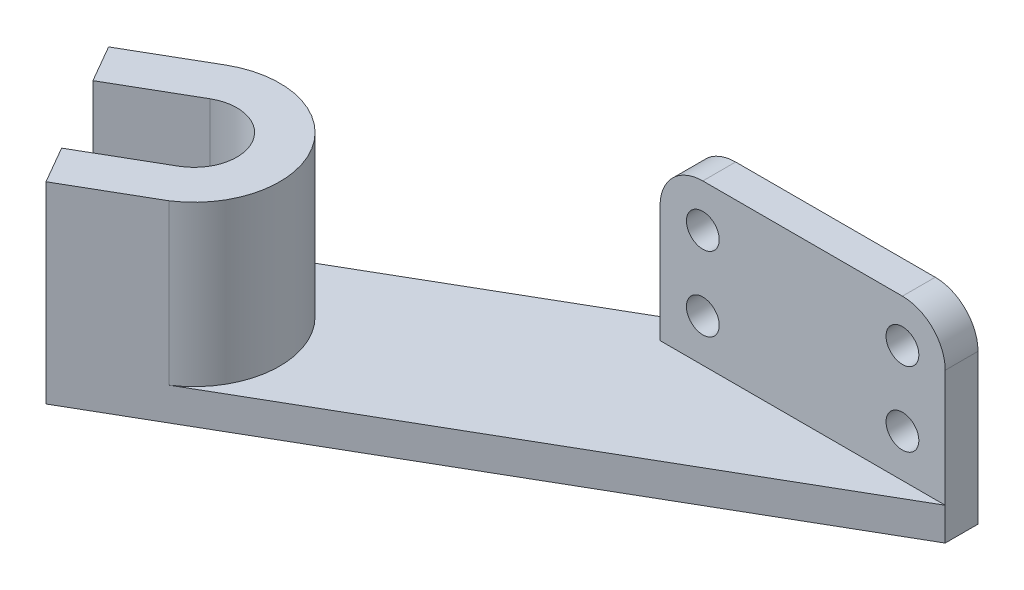
SolidWorks part; units mm, degrees
ref_plane "前视基准面" through (0, 0, 0) normal (0, 0, 1) x (1, 0, 0)
ref_plane "上视基准面" through (0, 0, 0) normal (0, 1, 0) x (1, 0, 0)
ref_plane "右视基准面" through (0, 0, 0) normal (1, 0, 0) x (0, 0, -1)
sketch "草图1" plane through (0, 0, 0) normal (0, 0, 1) x (1, 0, 0)
  line L1 (-50, 33.75) -> (50, 33.75)
  line L2 (-50, 33.75) -> (-50, -33.75)
  line L3 (-50, -33.75) -> (50, -33.75)
  line L4 (50, 33.75) -> (50, -33.75)
  line L5 (-50, 33.75) -> (50, -33.75) construction
  line L6 (-50, -33.75) -> (50, 33.75) construction
  point P0 (0, 0)
  dimension "D1" = 100
  dimension "D2" = 67.5
extrude "凸台-拉伸1" add sketch "草图1" along normal mid plane 11.5
fillet "圆角1" radius 15 2 edges at (50, 33.75, 0) (-50, 33.75, 0)
hole_wizard "Ø11.5 (11.5) 直径孔1" positions "草图2" profile "草图3" hole size "Ø11.5" standard "GB" end condition through all
sketch "草图2" plane through (0, 0, 5.75) normal (0, 0, 1) x (1, 0, 0)
  line L8 (50, -33.75) -> (50, 18.75)
  line L9 (35, 33.75) -> (-35, 33.75)
  line L10 (-50, 18.75) -> (-50, -33.75)
  line L11 (-50, -33.75) -> (50, -33.75)
  line L12 (50, -33.75) -> (50, 18.75)
  line L13 (35, 33.75) -> (-35, 33.75)
  line L14 (-50, 18.75) -> (-50, -33.75)
  line L15 (-50, -33.75) -> (50, -33.75)
  arc A4 (50, 18.75) -> (35, 33.75) centre (35, 18.75) ccw
  arc A5 (-35, 33.75) -> (-50, 18.75) centre (-35, 18.75) ccw
  arc A6 (50, 18.75) -> (35, 33.75) centre (35, 18.75) ccw
  arc A7 (-35, 33.75) -> (-50, 18.75) centre (-35, 18.75) ccw
  point P0 (-35, 18.75)
  point P2 (35, 18.75)
  point P4 (-35, -7.25)
  point P6 (35, -7.25)
  point P39 (0, 0)
  point P44 (-53.5504, 12.9775)
  point P45 (0, 0)
  dimension "D1" = 70
  dimension "D2" = 26.5
  dimension "D4" = 52.5
  dimension "D3" = 0
sketch "草图3" plane through (-35, 18.75, 5.75) normal (1, 0, 0) x (0, -1, 0)
  line L0 (0, 0) -> (0, 11.5)
  line L1 (0, 11.5) -> (5.75, 11.5)
  line L2 (5.75, 11.5) -> (5.75, 0)
  line L5 (5.75, 0) -> (0, 0)
  line L11 (0, -6.35) -> (0, 107.95) construction
  point P3 (0, 0)
  dimension "通孔孔直径" = 11.5
  dimension "通孔孔深度" = 11.5
sketch "草图5" plane through (0, -33.75, 0) normal (0, -1, 0) x (1, 0, 0)
  line L0 (-179.9038, 69.25) -> (-50, -5.75)
  line L1 (-179.9038, 69.25) -> (-172.4038, 82.2404)
  line L2 (-172.4038, 82.2404) -> (-146.423, 67.2404)
  line L3 (50, 5.75) -> (-149.9242, 121.1763)
  line L4 (-131.423, 93.2211) -> (-157.4038, 108.2211)
  line L5 (-157.4038, 108.2211) -> (-149.9242, 121.1763)
  line L6 (-50, -5.75) -> (-50, 5.75)
  line L7 (-50, 5.75) -> (50, 5.75)
  arc A0 (-146.423, 67.2404) -> (-131.423, 93.2211) centre (-138.923, 80.2308) ccw
  arc A1 (-122.5904, 105.3951) -> (-125.2964, 106.9574) centre (-138.923, 80.2308) ccw
  dimension "D4" = 30
  dimension "D6" = 30
  dimension "D3" = 150
extrude "凸台-拉伸2" add sketch "草图5" against normal blind 11.5 contours L3 L5 L4 A0 L2 L1 L0 L6 L7
sketch "草图6" plane through (0, -22.25, 0) normal (0, 1, 0) x (1, 0, 0)
  line L8 (50, -5.75) -> (-50, -5.75)
  line L9 (-50, -5.75) -> (-50, 5.75)
  line L10 (-50, 5.75) -> (-179.9038, -69.25)
  line L11 (-179.9038, -69.25) -> (-172.4038, -82.2404)
  line L12 (-172.4038, -82.2404) -> (-146.423, -67.2404)
  line L13 (-131.423, -93.2211) -> (-157.4038, -108.2211)
  line L14 (-157.4038, -108.2211) -> (-149.9242, -121.1763)
  line L15 (-149.9242, -121.1763) -> (50, -5.75)
  line L16 (50, -5.75) -> (-50, -5.75)
  line L17 (-50, -5.75) -> (-50, 5.75)
  line L18 (-50, 5.75) -> (-179.9038, -69.25)
  line L19 (-179.9038, -69.25) -> (-172.4038, -82.2404)
  line L20 (-172.4038, -82.2404) -> (-146.423, -67.2404)
  line L21 (-131.423, -93.2211) -> (-157.4038, -108.2211)
  line L22 (-157.4038, -108.2211) -> (-149.9242, -121.1763)
  line L23 (-149.9242, -121.1763) -> (50, -5.75)
  arc A0 (-125.2964, -106.9574) -> (-153.923, -54.25) centre (-138.923, -80.2308) ccw
  arc A1 (-131.423, -93.2211) -> (-146.423, -67.2404) centre (-138.923, -80.2308) ccw
  arc A2 (-131.423, -93.2211) -> (-146.423, -67.2404) centre (-138.923, -80.2308) ccw
  line M14 (-179.9038, -69.25) -> (-172.4038, -82.2404)
  line M15 (-172.4038, -82.2404) -> (-146.423, -67.2404)
  arc M16 (-146.423, -67.2404) -> (-131.423, -93.2211) centre (-138.923, -80.2308) cw
  line M17 (-131.423, -93.2211) -> (-157.4038, -108.2211)
  line M18 (-157.4038, -108.2211) -> (-149.9242, -121.1763)
  line M19 (-149.9242, -121.1763) -> (50, -5.75)
  dimension "D1" = 0
extrude "凸台-拉伸3" add sketch "草图6" along normal blind 56 contours L23 A0 L18 M14 M15 M16 M17 M18 M19
